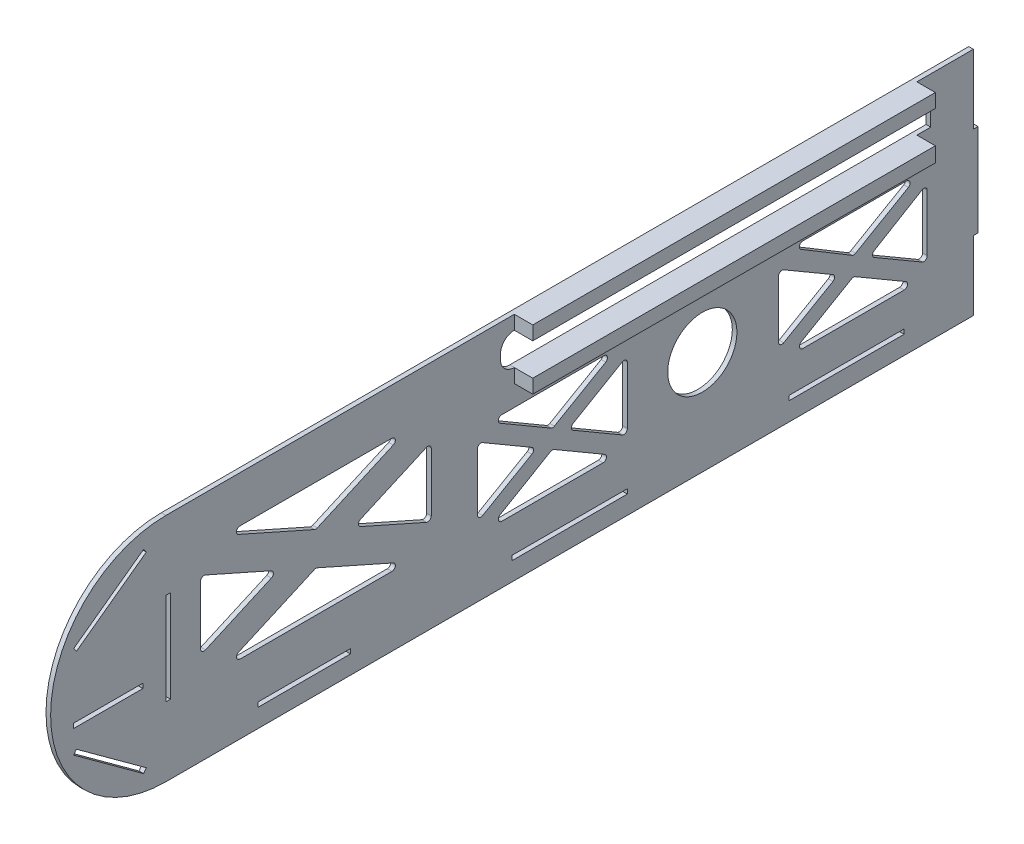
SolidWorks part; units mm, degrees
ref_plane "前视基准面" through (0, 0, 0) normal (0, 0, 1) x (1, 0, 0)
ref_plane "上视基准面" through (0, 0, 0) normal (0, 1, 0) x (1, 0, 0)
ref_plane "右视基准面" through (0, 0, 0) normal (1, 0, 0) x (0, 0, -1)
sketch "草图1" plane through (0, 0, 0) normal (1, 0, 0) x (0, 0, -1)
  line L0 (145, 38) -> (145, 36)
  line L1 (0, 50) -> (139, 50)
  line L2 (0, 50) -> (0, -50)
  line L3 (0, -50) -> (350, -50)
  line L4 (350, 50) -> (350, -50)
  line L5 (145, 50) -> (331.5, 50)
  line L6 (151, 30) -> (325.5, 30)
  line L7 (331.5, 38) -> (331.5, 36)
  line L8 (337.5, 50) -> (350, 50)
  line L9 (84.3341, 3.6293) -> (112.8908, -9.0626)
  line L10 (-40, -10) -> (-10, -10)
  line L11 (-40, -10) -> (-40, -8)
  line L12 (-40, -8) -> (-10, -8)
  line L13 (-10, -10) -> (-10, -8)
  line L14 (32.0683, 30) -> (97.9317, 30)
  line L15 (15, 17.6919) -> (15, -7.6919)
  line L16 (32.0683, -20) -> (97.9317, -20)
  line L17 (115, 17.6919) -> (115, -7.6919)
  line L18 (17.1092, 19.0626) -> (45.6659, 6.3707)
  line L19 (17.1092, -9.0626) -> (45.6659, 3.6293)
  line L20 (84.3341, 6.3707) -> (112.8908, 19.0626)
  line L21 (31.4591, 27.1293) -> (64.3908, 12.493)
  line L22 (145.5484, 15) -> (189.8851, 15)
  line L23 (135, 7.3884) -> (135, -17.3987)
  line L24 (145.5484, -25) -> (189.4516, -25)
  line L25 (200, 7.3884) -> (200, -17.3884)
  line L26 (65.6092, 12.493) -> (98.5409, 27.1293)
  line L27 (31.4591, -17.1293) -> (64.3908, -2.493)
  line L28 (65.6092, -2.493) -> (98.5409, -17.1293)
  line L29 (176.5069, -6.2957) -> (197.7442, -18.6841)
  line L30 (158.585, -3.7579) -> (137.2558, 8.6841)
  line L31 (137.2514, -18.6969) -> (158.5806, -6.3518)
  line L32 (176.5069, -3.7043) -> (197.7442, 8.6841)
  line L33 (144.7926, 12.2043) -> (166.8743, -0.6766)
  line L34 (190.6365, 12.2018) -> (168.3815, -0.6792)
  line L35 (168.2558, -9.3992) -> (190.2074, -22.2043)
  line L36 (144.7926, -22.2043) -> (166.7442, -9.3992)
  line L37 (276.0709, 15) -> (321.089, 15)
  line L38 (265.5225, 6.9941) -> (265.5225, -17.793)
  line L39 (276.0709, -25.3943) -> (319.9742, -25.3943)
  line L40 (330, 6.9941) -> (330, -17.478)
  line L41 (307.0294, -6.69) -> (327.7442, -18.7736)
  line L42 (289.1076, -4.1523) -> (267.7784, 8.2898)
  line L43 (267.7739, -19.0912) -> (289.1032, -6.7462)
  line L44 (307.0153, -4.107) -> (327.7301, 8.2815)
  line L45 (275.2981, 12.2144) -> (297.3797, -1.0609)
  line L46 (321.8404, 12.2018) -> (298.904, -1.0735)
  line L47 (298.7784, -9.7935) -> (320.73, -22.5987)
  line L48 (275.3151, -22.5987) -> (297.2667, -9.7935)
  line L49 (-40, 20) -> (-9.6982, 42.0918)
  line L50 (-40, 20) -> (-38.8218, 18.3839)
  line L51 (-9.6982, 42.0918) -> (-8.5199, 40.4757)
  line L52 (-38.8218, 18.3839) -> (-8.5199, 40.4757)
  line L53 (-50, 0) -> (0, 0)
  line L54 (-38.8218, -18.3839) -> (-8.5199, -40.4757)
  line L55 (-9.6982, -42.0918) -> (-8.5199, -40.4757)
  line L56 (-40, -20) -> (-38.8218, -18.3839)
  line L57 (-40, -20) -> (-9.6982, -42.0918)
  line L58 (40, -40) -> (80, -40)
  line L59 (40, -40) -> (40, -42)
  line L60 (80, -40) -> (80, -42)
  line L61 (40, -42) -> (80, -42)
  line L62 (150, -40) -> (200, -40)
  line L63 (150, -40) -> (150, -42)
  line L64 (200, -40) -> (200, -42)
  line L65 (150, -42) -> (200, -42)
  line L66 (270, -40) -> (320, -40)
  line L67 (270, -40) -> (270, -42)
  line L68 (320, -40) -> (320, -42)
  line L69 (270, -42) -> (320, -42)
  line L70 (350, 20) -> (352, 20)
  line L71 (350, 20) -> (350, -20)
  line L72 (352, 20) -> (352, -20)
  line L73 (350, -20) -> (352, -20)
  line L74 (0, 20) -> (0, -20)
  line L75 (0, 20) -> (2, 20)
  line L76 (0, -20) -> (2, -20)
  line L77 (2, 20) -> (2, -20)
  line L78 (139, 50) -> (145, 50)
  line L79 (331.5, 50) -> (337.5, 50)
  line L80 (151, 44) -> (325.5, 44)
  line L81 (151, 30) -> (151, 44)
  line L82 (145, 44) -> (145, 28)
  line L83 (151, 22) -> (325.5, 22)
  line L84 (331.5, 28) -> (331.5, 44)
  line L85 (325.5, 30) -> (331.5, 30)
  arc A0 (0, 50) -> (0, -50) centre (0, 0) ccw
  arc A1 (139, 50) -> (145, 44) centre (139, 44) cw
  arc A3 (151, 30) -> (145, 36) centre (151, 36) cw
  arc A4 (337.5, 50) -> (331.5, 44) centre (337.5, 44) ccw
  arc A5 (17.1092, 19.0626) -> (15, 17.6919) centre (16.5, 17.6919) ccw
  arc A6 (15, -7.6919) -> (17.1092, -9.0626) centre (16.5, -7.6919) ccw
  arc A7 (45.6659, 3.6293) -> (45.6659, 6.3707) centre (45.0567, 5) ccw
  arc A8 (84.3341, 6.3707) -> (84.3341, 3.6293) centre (84.9433, 5) ccw
  arc A9 (112.8908, -9.0626) -> (115, -7.6919) centre (113.5, -7.6919) ccw
  arc A10 (115, 17.6919) -> (112.8908, 19.0626) centre (113.5, 17.6919) ccw
  arc A11 (31.4591, -17.1293) -> (32.0683, -20) centre (32.0683, -18.5) ccw
  arc A12 (97.9317, -20) -> (98.5409, -17.1293) centre (97.9317, -18.5) ccw
  arc A13 (65.6092, -2.493) -> (64.3908, -2.493) centre (65, -3.8637) ccw
  arc A14 (97.9317, 30) -> (98.5409, 27.1293) centre (97.9317, 28.5) cw
  arc A15 (65.6092, 12.493) -> (64.3908, 12.493) centre (65, 13.8637) cw
  arc A16 (31.4591, 27.1293) -> (32.0683, 30) centre (32.0683, 28.5) cw
  arc A17 (197.7442, 8.6841) -> (200, 7.3884) centre (198.5, 7.3884) cw
  arc A18 (200, -17.3884) -> (197.7442, -18.6841) centre (198.5, -17.3884) cw
  arc A19 (176.5069, -6.2957) -> (176.5069, -3.7043) centre (177.2627, -5) cw
  arc A20 (158.585, -3.7579) -> (158.5806, -6.3518) centre (157.8292, -5.0536) cw
  arc A21 (137.2514, -18.6969) -> (135, -17.3987) centre (136.5, -17.3987) cw
  arc A22 (135, 7.3884) -> (137.2558, 8.6841) centre (136.5, 7.3884) cw
  arc A23 (144.7926, -22.2043) -> (145.5484, -25) centre (145.5484, -23.5) ccw
  arc A24 (189.4516, -25) -> (190.2074, -22.2043) centre (189.4516, -23.5) ccw
  arc A25 (168.2558, -9.3992) -> (166.7442, -9.3992) centre (167.5, -10.6949) ccw
  arc A26 (144.7926, 12.2043) -> (145.5484, 15) centre (145.5484, 13.5) cw
  arc A27 (189.8851, 15) -> (190.6365, 12.2018) centre (189.8851, 13.5) cw
  arc A28 (168.3815, -0.6792) -> (166.8743, -0.6766) centre (167.6301, 0.619) cw
  arc A29 (327.7301, 8.2815) -> (330, 6.9941) centre (328.5, 6.9941) cw
  arc A30 (330, -17.478) -> (327.7442, -18.7736) centre (328.5, -17.478) cw
  arc A31 (307.0294, -6.69) -> (307.0153, -4.107) centre (307.7852, -5.3943) cw
  arc A32 (289.1076, -4.1523) -> (289.1032, -6.7462) centre (288.3518, -5.4479) cw
  arc A33 (267.7739, -19.0912) -> (265.5225, -17.793) centre (267.0225, -17.793) cw
  arc A34 (265.5225, 6.9941) -> (267.7784, 8.2898) centre (267.0225, 6.9941) cw
  arc A35 (275.3151, -22.5987) -> (276.0709, -25.3943) centre (276.0709, -23.8943) ccw
  arc A36 (319.9742, -25.3943) -> (320.73, -22.5987) centre (319.9742, -23.8943) ccw
  arc A37 (298.7784, -9.7935) -> (297.2667, -9.7935) centre (298.0225, -11.0892) ccw
  arc A38 (275.2981, 12.2144) -> (276.0709, 15) centre (276.0709, 13.5) cw
  arc A39 (321.089, 15) -> (321.8404, 12.2018) centre (321.089, 13.5) cw
  arc A40 (298.904, -1.0735) -> (297.3797, -1.0609) centre (298.1526, 0.2247) cw
  circle A41 centre (232.5, -5) radius 15
  arc A42 (151, 22) -> (145, 28) centre (151, 28) cw
  arc A43 (331.5, 28) -> (325.5, 22) centre (325.5, 28) cw
  arc A44 (331.5, 38) -> (325.5, 44) centre (325.5, 38) ccw
  arc A45 (151, 44) -> (145, 38) centre (151, 38) ccw
  point P5 (145, 30)
  point P6 (145, 50)
  point P7 (331.5, 30)
  point P8 (331.5, 50)
  point P21 (145, 30)
  point P32 (105, 30)
  point P33 (25, 30)
  point P34 (25, -20)
  point P35 (105, -20)
  point P36 (65, 5)
  point P37 (115, 20)
  point P38 (15, -10)
  point P39 (15, 20)
  point P40 (115, -10)
  point P49 (48.75, 5)
  point P50 (65, -2.2222)
  point P51 (81.25, 5)
  point P52 (65, 12.2222)
  point P53 (140, 15)
  point P58 (195.4712, 15)
  point P59 (140, -25)
  point P60 (195, -25)
  point P61 (140, -25)
  point P62 (135, -20)
  point P63 (200, -20)
  point P64 (200, 10)
  point P65 (135, 10)
  point P86 (65, -2.2222)
  point P90 (65, 12.2222)
  point P124 (270.5225, 15)
  point P129 (325.9937, 15)
  point P130 (270.5225, -25.3943)
  point P131 (325.5225, -25.3943)
  point P132 (270.5225, -25.3943)
  point P133 (265.5225, -20.3943)
  point P134 (330, -20.3943)
  point P135 (330, 9.6057)
  point P136 (265.5225, 9.6057)
  point P169 (350, -20)
  point P182 (-9.6982, -42.0918)
  point P184 (-40, -20)
  point P189 (352, 20)
  point P190 (352, -20)
  point P198 (350, 20)
  point P209 (145, 22)
  dimension "D1" = 6
  dimension "D3" = 6
  dimension "D4" = 6
  dimension "D5" = 1.5
  dimension "D6" = 1.5
  dimension "D7" = 1.5
  dimension "D8" = 1.5
  dimension "D9" = 1.5
  dimension "D10" = 1.5
  dimension "D11" = 1.5
  dimension "D12" = 1.5
  dimension "D13" = 1.5
  dimension "D14" = 1.5
  dimension "D15" = 1.5
  dimension "D16" = 1.5
  dimension "D17" = 1.5
  dimension "D18" = 1.5
  dimension "D19" = 1.5
  dimension "D20" = 1.5
  dimension "D21" = 1.5
  dimension "D22" = 1.5
  dimension "D23" = 1.5
  dimension "D24" = 1.5
  dimension "D25" = 1.5
  dimension "D26" = 1.5
  dimension "D27" = 1.5
  dimension "D28" = 1.5
  dimension "D29" = 1.5
  dimension "D30" = 1.5
  dimension "D31" = 1.5
  dimension "D32" = 1.5
  dimension "D33" = 1.5
  dimension "D34" = 1.5
  dimension "D35" = 1.5
  dimension "D36" = 1.5
  dimension "D37" = 1.5
  dimension "D38" = 1.5
  dimension "D39" = 1.5
  dimension "D40" = 1.5
  dimension "D41" = 2
  dimension "D44" = 14
  dimension "D46" = 6
  dimension "D47" = 6
  dimension "D48" = 6
  dimension "D42" = 37.5
  dimension "D43" = 2
  dimension "D45" = 22
extrude "凸台-拉伸3" add sketch "草图1" along normal blind 2 contours L2 A0 L53 L52 L50 L49 L51 | L53 A0 L2 L57 L56 L54 L55 L13 L10 L11 L12 | L84 A43 L83 A42 L82 L0 A1 L1 L2 L75 L77 L76 L3 L4 L8 A4 L7 A41 A37 L47 A36 L39 A35 L48 A25 L35 A24 L24 A23 L36 A13 L28 A12 L16 A11 L27 A10 L17 A9 L9 | A45 L80 A44 L84 A4 L79 L5 L78 A1 L82 | A43 L84 L85 L6 A3 L82 A42 L83 | L4 L73 L72 L70
sketch "草图2" plane through (0, 0, 0) normal (1, 0, 0) x (0, 0, -1)
  line L0 (151, 44) -> (325.5, 44)
  line L1 (325.5, 44) -> (325.5, 50)
  line L2 (0, 50) -> (350, 50) construction
  line L3 (325.5, 50) -> (151, 50)
  line L4 (151, 50) -> (151, 44)
  line L5 (151, 30) -> (151, 24)
  line L6 (325.5, 23.5604) -> (325.5, 30)
  line L7 (151, 30) -> (331.5, 30) construction
  line L8 (325.5, 30) -> (151, 30)
  line L9 (151, 24) -> (325.5, 23.5604)
extrude "凸台-拉伸4" add sketch "草图2" along normal blind 10 contours L9 L6 L8 L5 | L4 L0 L1 L3
